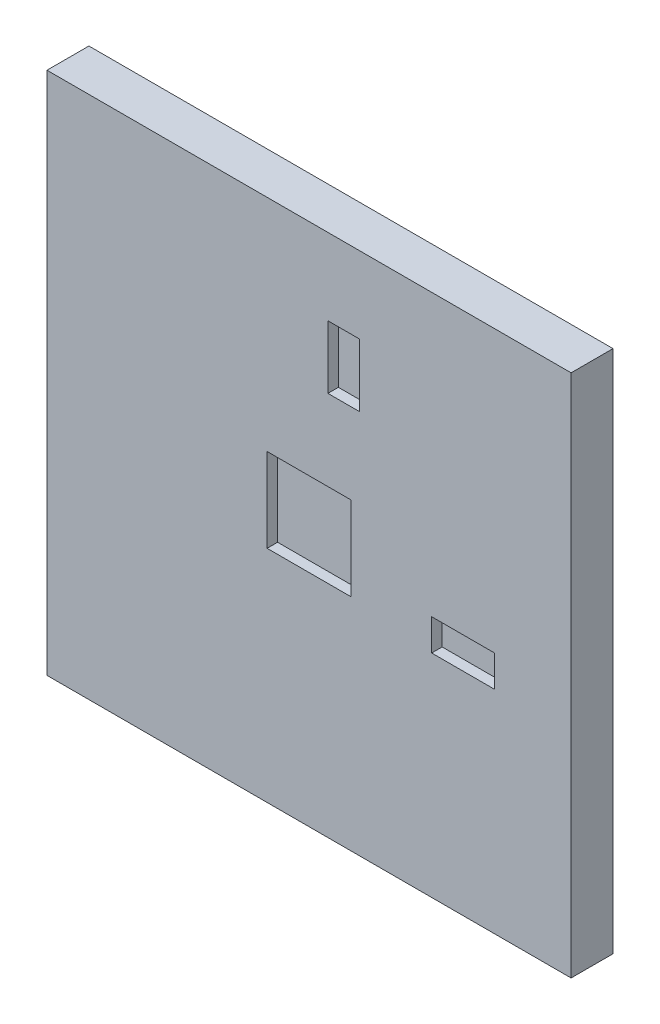
SolidWorks part; units mm, degrees
material "PVC 0.007 Plasticized"
ref_plane "Ön Düzlem" through (0, 0, 0) normal (0, 0, 1) x (1, 0, 0)
ref_plane "Üst Düzlem" through (0, 0, 0) normal (0, 1, 0) x (1, 0, 0)
ref_plane "Sağ Düzlem" through (0, 0, 0) normal (1, 0, 0) x (0, 0, -1)
sketch "Sketch1" plane through (0, 0, 0) normal (0, 0, 1) x (1, 0, 0)
  line L1 (147.0484, -195.9037) -> (-102.9516, -195.9037)
  line L2 (147.0484, -195.9037) -> (147.0484, 54.0963)
  line L3 (147.0484, 54.0963) -> (-102.9516, 54.0963)
  line L4 (-102.9516, -195.9037) -> (-102.9516, 54.0963)
  dimension "D1" = 250
  dimension "D2" = 250
extrude "Boss-Extrude1" add sketch "Sketch1" along normal blind 20
sketch "Sketch2" plane through (0, 0, 20) normal (0, 0, 1) x (1, 0, 0)
  line L0 (147.0484, -195.9037) -> (147.0484, 54.0963) construction
  line L1 (31.0484, 17.5963) -> (46.0484, 17.5963)
  line L2 (31.0484, 17.5963) -> (31.0484, -12.4037)
  line L3 (31.0484, -12.4037) -> (46.0484, -12.4037)
  line L4 (46.0484, 17.5963) -> (46.0484, -12.4037)
  line L5 (80.5484, -94.9037) -> (110.5484, -94.9037)
  line L6 (80.5484, -94.9037) -> (80.5484, -79.9037)
  line L7 (80.5484, -79.9037) -> (110.5484, -79.9037)
  line L8 (110.5484, -94.9037) -> (110.5484, -79.9037)
  line L9 (2.0484, -50.9037) -> (42.0484, -50.9037)
  line L10 (2.0484, -50.9037) -> (2.0484, -90.9037)
  line L11 (2.0484, -90.9037) -> (42.0484, -90.9037)
  line L12 (42.0484, -50.9037) -> (42.0484, -90.9037)
  line L13 (-102.9516, -195.9037) -> (147.0484, -195.9037) construction
  line L14 (-102.9516, 54.0963) -> (-102.9516, -195.9037) construction
  line L15 (147.0484, 54.0963) -> (-102.9516, 54.0963) construction
  dimension "D1" = 15
  dimension "D2" = 30
  dimension "D3" = 30
  dimension "D4" = 15
  dimension "D5" = 40
  dimension "D6" = 40
  dimension "D7" = 101
  dimension "D8" = 36.5
  dimension "D9" = 101
  dimension "D10" = 105
  dimension "D11" = 105
  dimension "D12" = 36.5
extrude "Cut-Extrude1" cut sketch "Sketch2" against normal blind 5
